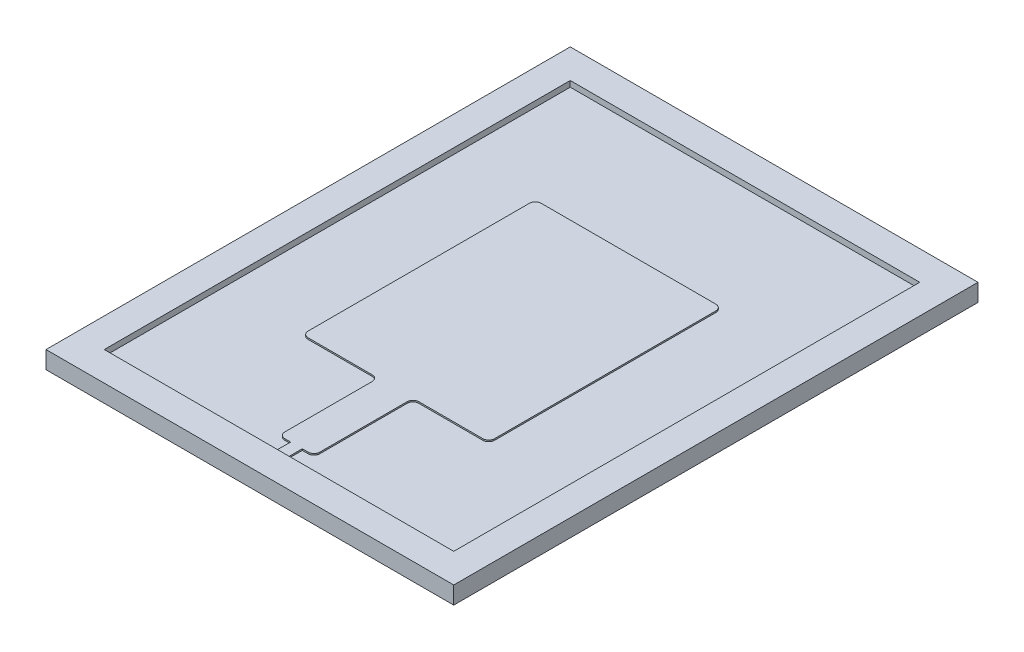
SolidWorks part; units mm, degrees
ref_plane "Front Plane" through (0, 0, 0) normal (0, 0, 1) x (1, 0, 0)
ref_plane "Top Plane" through (0, 0, 0) normal (0, 1, 0) x (1, 0, 0)
ref_plane "Right Plane" through (0, 0, 0) normal (1, 0, 0) x (0, 0, -1)
sketch "Sketch1" plane through (0, 0, 0) normal (0, 1, 0) x (1, 0, 0)
  line L1 (-17.5, 22.5) -> (17.5, 22.5)
  line L2 (-17.5, 22.5) -> (-17.5, -22.5)
  line L3 (-17.5, -22.5) -> (17.5, -22.5)
  line L4 (17.5, 22.5) -> (17.5, -22.5)
  dimension "D1" = 35
  dimension "D2" = 17.5
  dimension "D3" = 45
  dimension "D4" = 22.5
extrude "Boss-Extrude1" add sketch "Sketch1" along normal blind 1.5
sketch "Sketch2" plane through (0, 1.5, 0) normal (0, 1, 0) x (1, 0, 0)
  line L8 (-15, 20) -> (-15, -20)
  line L9 (-15, -20) -> (15, -20)
  line L10 (15, -20) -> (15, 20)
  line L11 (15, 20) -> (-15, 20)
  line L12 (-15, 20) -> (-15, -20)
  line L13 (-15, -20) -> (15, -20)
  line L14 (15, -20) -> (15, 20)
  line L15 (15, 20) -> (-15, 20)
  dimension "D1" = 2.5
extrude "Cut-Extrude1" cut sketch "Sketch2" against normal blind 0.5
sketch "Sketch3" plane through (0, 1, 0) normal (0, 1, 0) x (1, 0, 0)
  line L0 (-1.5, -10.5) -> (-1.5, -18)
  line L1 (-7.5, 10) -> (7.5, 10)
  line L2 (-8, 9.5) -> (-8, -9.5)
  line L3 (-7.5, -10) -> (-2, -10)
  line L4 (8, 9.5) -> (8, -9.5)
  line L6 (1.5, -10.5) -> (1.5, -18)
  line L7 (-15, -20) -> (15, -20) construction
  line L8 (2, -10) -> (7.5, -10)
  line L9 (-0.5, -18.5) -> (-0.5, -20)
  line L10 (-1, -18.5) -> (-0.5, -18.5)
  line L11 (-15, -20) -> (15, -20) construction
  line L12 (0.5, -18.5) -> (0.5, -20)
  line L13 (-0.5, -20) -> (0.5, -20)
  line L14 (0.5, -18.5) -> (1, -18.5)
  arc A0 (1, -18.5) -> (1.5, -18) centre (1, -18) ccw
  arc A1 (-1, -18.5) -> (-1.5, -18) centre (-1, -18) cw
  arc A2 (-1.5, -10.5) -> (-2, -10) centre (-2, -10.5) ccw
  arc A3 (1.5, -10.5) -> (2, -10) centre (2, -10.5) cw
  arc A4 (-7.5, 10) -> (-8, 9.5) centre (-7.5, 9.5) ccw
  arc A5 (-8, -9.5) -> (-7.5, -10) centre (-7.5, -9.5) ccw
  arc A6 (7.5, -10) -> (8, -9.5) centre (7.5, -9.5) ccw
  arc A7 (7.5, 10) -> (8, 9.5) centre (7.5, 9.5) cw
  point P19 (1.5, -10)
  point P22 (-8, 10)
  point P27 (8, -10)
  point P30 (8, 10)
  dimension "D8" = 0.5
  dimension "D1" = 16
  dimension "D2" = 8
  dimension "D3" = 20
  dimension "D4" = 10
  dimension "D5" = 1.5
  dimension "D6" = 1.5
  dimension "D7" = 1.5
  dimension "D9" = 1
  dimension "D10" = 1
extrude "Boss-Extrude2" add sketch "Sketch3" along normal blind 0.125
